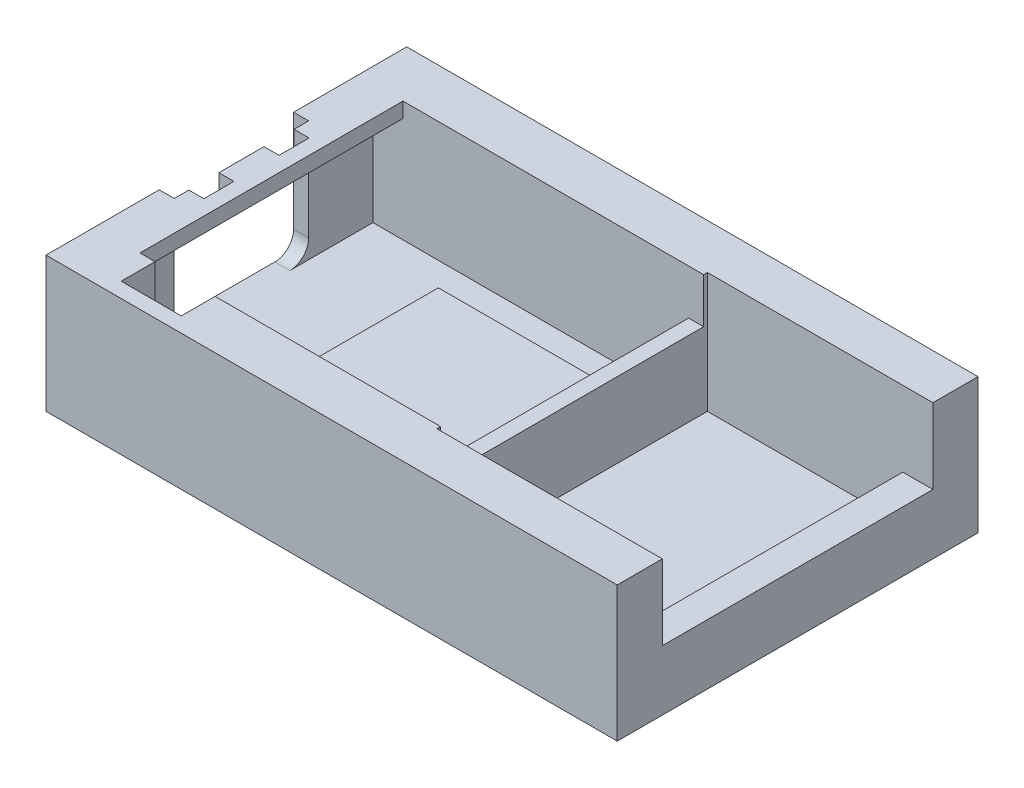
SolidWorks part; units mm, degrees
ref_plane "Front Plane" through (0, 0, 0) normal (0, 0, 1) x (1, 0, 0)
ref_plane "Top Plane" through (0, 0, 0) normal (0, 1, 0) x (1, 0, 0)
ref_plane "Right Plane" through (0, 0, 0) normal (1, 0, 0) x (0, 0, -1)
sketch "Sketch1" plane through (0, 0, 0) normal (0, 1, 0) x (1, 0, 0)
  line L1 (0, 0) -> (40, 0)
  line L2 (0, 0) -> (0, 24)
  line L3 (0, 24) -> (40, 24)
  line L4 (40, 0) -> (40, 24)
  dimension "D1" = 24
  dimension "D2" = 40
extrude "Boss-Extrude1" add sketch "Sketch1" along normal blind 1
sketch "Sketch2" plane through (0, 1, 0) normal (0, 1, 0) x (1, 0, 0)
  line L1 (0, 24) -> (40, 24)
  line L2 (0, 24) -> (0, 0)
  line L3 (0, 0) -> (40, 0)
  line L4 (40, 24) -> (40, 0)
  line L5 (1, 20.75) -> (22, 20.75)
  line L6 (1, 20.75) -> (1, 3.25)
  line L7 (1, 3.25) -> (22, 3.25)
  line L8 (22, 20.75) -> (22, 3.25)
  line L9 (23, 21) -> (36, 21)
  line L10 (23, 21) -> (23, 3)
  line L11 (23, 3) -> (36, 3)
  line L12 (36, 21) -> (36, 3)
  dimension "D1" = 17.5
  dimension "D2" = 21
  dimension "D3" = 3.25
  dimension "D4" = 1
  dimension "D5" = 18
  dimension "D6" = 13
  dimension "D7" = 1
  dimension "D8" = 3
extrude "Boss-Extrude3" add sketch "Sketch2" along normal blind 8
sketch "Sketch3" plane through (0, 9, 0) normal (0, 1, 0) x (1, 0, 0)
  line L0 (22, 20.75) -> (23, 20.75)
  line L1 (23, 21) -> (23, 3) construction
  line L2 (22, 20.75) -> (22, 3.25)
  line L3 (22, 3.25) -> (23, 3.25)
  line L4 (23, 21) -> (23, 3) construction
  line L5 (23, 3.25) -> (23, 20.75)
extrude "Cut-Extrude2" cut sketch "Sketch3" against normal blind 3
sketch "Sketch4" plane through (0, 1, 0) normal (0, 1, 0) x (1, 0, 0)
  line L0 (22, 20.75) -> (22, 3.25) construction
  line L1 (8.14, 17.96) -> (18.38, 17.96)
  line L2 (8.14, 17.96) -> (8.14, 6.04)
  line L3 (8.14, 6.04) -> (18.38, 6.04)
  line L4 (18.38, 17.96) -> (18.38, 6.04)
  line L5 (22, 20.75) -> (1, 20.75) construction
  line L6 (1, 3.25) -> (22, 3.25) construction
  line L7 (1, 20.75) -> (1, 3.25) construction
  dimension "D1" = 3.62
  dimension "D2" = 2.79
  dimension "D3" = 2.79
  dimension "D4" = 7.14
extrude "Boss-Extrude4" add sketch "Sketch4" along normal blind 1.21
sketch "Sketch5" plane through (1, 0, 0) normal (1, 0, 0) x (0, 0, -1)
  line L0 (7.53, 2.25) -> (7.53, 2.96)
  line L1 (8.78, 1) -> (15.22, 1)
  line L3 (16.47, 2.96) -> (16.47, 2.25)
  line L4 (20.75, 1) -> (3.25, 1) construction
  line L5 (3.25, 9) -> (3.25, 1) construction
  line L6 (7.53, 2.96) -> (7.53, 9)
  line L7 (20.75, 9) -> (3.25, 9) construction
  line L8 (7.53, 9) -> (16.47, 9)
  line L9 (16.47, 9) -> (16.47, 2.96)
  line L10 (20.75, 9) -> (20.75, 1) construction
  arc A0 (7.53, 2.25) -> (8.78, 1) centre (8.78, 2.25) ccw
  arc A3 (15.22, 1) -> (16.47, 2.25) centre (15.22, 2.25) ccw
  dimension "D7" = 1.25
  dimension "D1" = 1.25
  dimension "D2" = 0.71
  dimension "D3" = 6.44
  dimension "D4" = 4.28
  dimension "D9" = 0.71
  dimension "D10" = 4.28
extrude "Cut-Extrude3" cut sketch "Sketch5" against normal blind 2
sketch "Sketch8" plane through (0, 9, 0) normal (0, 1, 0) x (1, 0, 0)
  line L0 (36, 21) -> (40, 21)
  line L1 (40, 0) -> (40, 24) construction
  line L2 (36, 3) -> (40, 3)
  line L3 (40, 3) -> (40, 21)
  line L4 (36, 21) -> (36, 3)
extrude "Cut-Extrude4" cut sketch "Sketch8" against normal blind 5
sketch "Sketch10" plane through (0, 9, 0) normal (0, 1, 0) x (1, 0, 0)
sketch "Sketch11" plane through (40, 0, 0) normal (1, 0, 0) x (0, 0, -1)
  line L0 (21, 9) -> (24, 9) construction
  line L1 (0, 0) -> (24, 0)
  line L2 (0, 0) -> (0, 9)
  line L3 (0, 9) -> (24, 9)
  line L4 (24, 0) -> (24, 9)
  line L5 (24, 9) -> (24, 0) construction
extrude "Cut-Extrude5" cut sketch "Sketch11" against normal blind 2
sketch "Sketch12" plane through (0, 9, 0) normal (0, 1, 0) x (1, 0, 0)
  line L0 (0, 24) -> (0, 16.47) construction
  line L1 (4, 1) -> (8, 1)
  line L2 (4, 1) -> (4, 4)
  line L3 (4, 4) -> (8, 4)
  line L4 (8, 1) -> (8, 4)
  line L5 (0, 0) -> (38, 0) construction
  dimension "D1" = 4
  dimension "D2" = 1
  dimension "D3" = 3
  dimension "D4" = 4
extrude "Cut-Extrude6" cut sketch "Sketch12" against normal blind 3
sketch "Sketch13" plane through (0, 9, 0) normal (0, 1, 0) x (1, 0, 0)
  line L0 (23, 20.75) -> (1, 20.75) construction
  line L3 (1, 20.75) -> (3, 20.75)
  line L5 (1, 3.25) -> (4, 3.25) construction
  line L8 (1, 3.25) -> (3, 3.25)
  line L10 (2, 13.5) -> (2, 15.5)
  line L14 (2, 8.5) -> (2, 10.5)
  line L15 (2, 13.5) -> (1, 13.5)
  line L17 (2, 10.5) -> (1, 10.5)
  line L18 (1, 13.5) -> (1, 10.5)
  line L19 (2, 15.5) -> (1, 15.5)
  line L22 (1, 15.5) -> (1, 16.47)
  line L23 (2, 8.5) -> (1, 8.5)
  line L26 (1, 8.5) -> (1, 7.53)
  line L28 (1, 7.53) -> (1, 3.25)
  line L30 (0, 7.53) -> (1, 7.53) construction
  line L31 (1, 20.75) -> (1, 16.47)
  line L32 (3, 20.75) -> (3, 3.25)
  dimension "D1" = 2.97
  dimension "D2" = 2
  dimension "D3" = 1
  dimension "D4" = 3
  dimension "D5" = 2
  dimension "D6" = 2
  dimension "D8" = 1
  dimension "D9" = 1
extrude "Boss-Extrude5" add sketch "Sketch13" against normal blind 1 contours L15 L18 L17 L14 L23 L26 L28 L8 L32 L3 L31 L22 L19 L10
